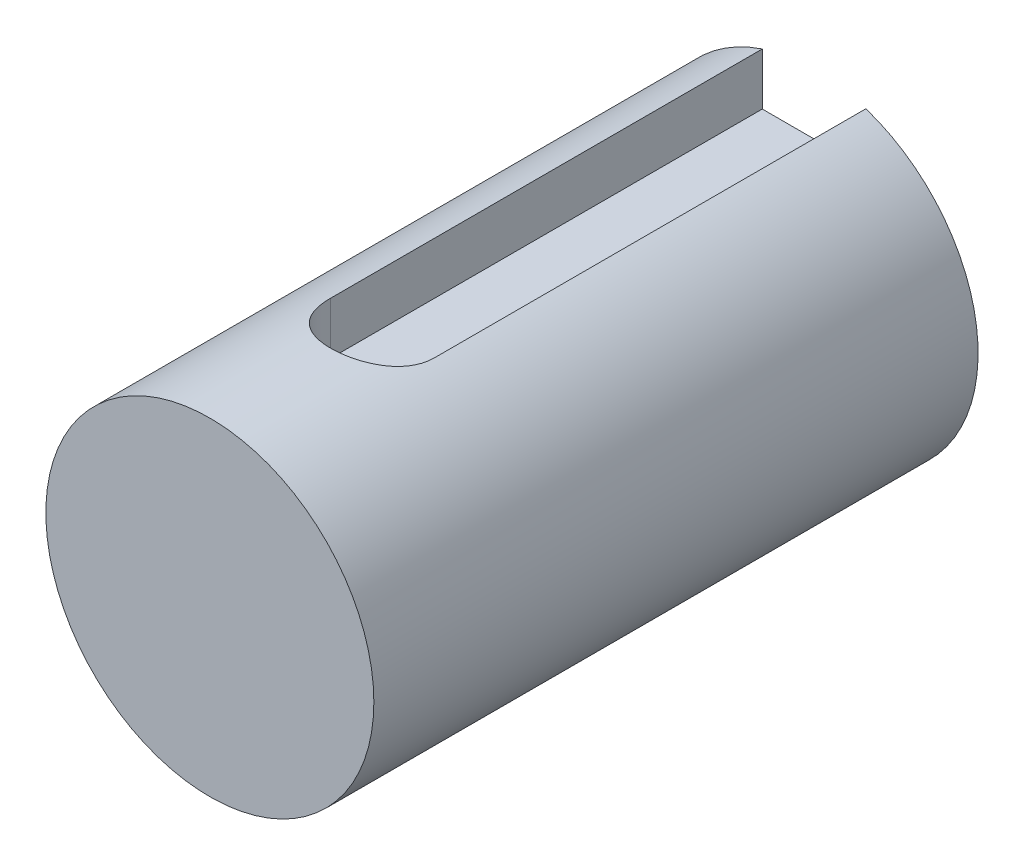
SolidWorks part; units mm, degrees
material "Plain Carbon Steel"
ref_plane "Front" through (0, 0, 0) normal (0, 0, 1) x (1, 0, 0)
ref_plane "Top" through (0, 0, 0) normal (0, 1, 0) x (1, 0, 0)
ref_plane "Right" through (0, 0, 0) normal (1, 0, 0) x (0, 0, -1)
sketch "Sketch1" plane through (0, 0, 0) normal (0, 0, 1) x (1, 0, 0)
  circle A0 centre (0, 0) radius 9.5
  dimension "D1" = 19
extrude "Boss-Extrude1" add sketch "Sketch1" along normal blind 35
ref_plane "Plane1" through (0, 10, 0) normal (0, 1, 0) x (1, 0, 0)
sketch "Sketch4" plane through (0, 10, 0) normal (0, 1, 0) x (1, 0, 0)
  line L0 (3, 0) -> (3, -25)
  line L1 (9.5, 0) -> (-9.5, 0) construction
  line L2 (-3, -25) -> (-3, 0)
  line L3 (-3, 0) -> (3, 0)
  arc A0 (3, -25) -> (-3, -25) centre (0, -25) cw
  dimension "D1" = 6
  dimension "D2" = 3
  dimension "D3" = 25
extrude "Cut-Extrude1" cut sketch "Sketch4" against normal blind 4
